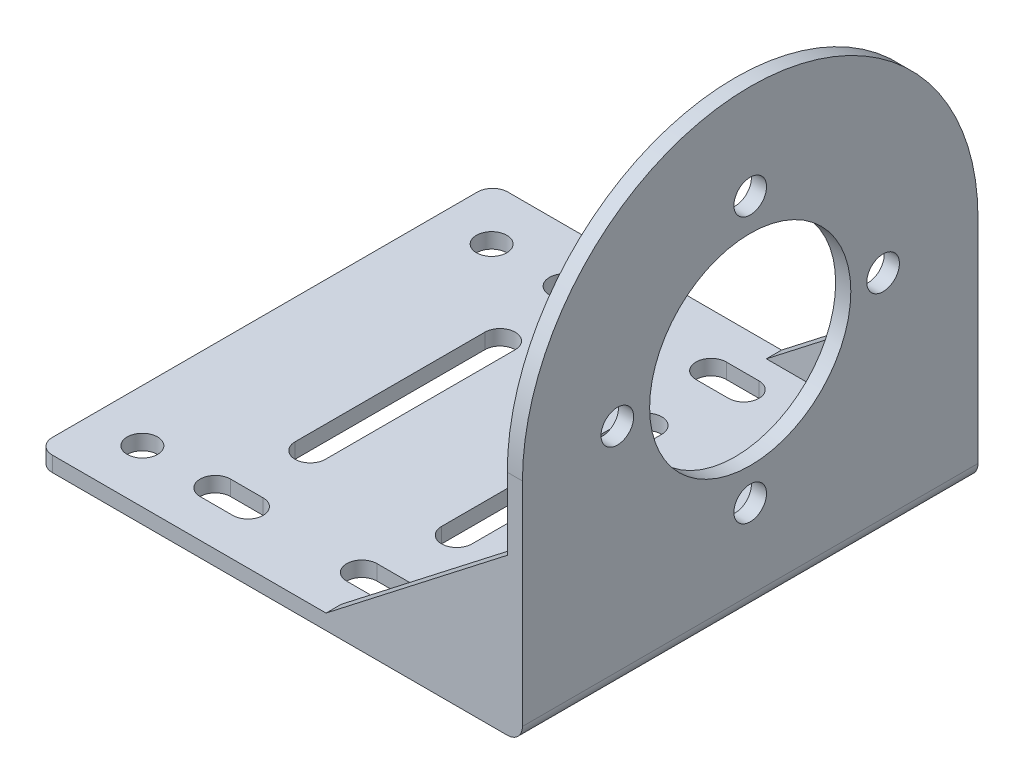
SolidWorks part; units mm, degrees
ref_plane "Front Plane" through (0, 0, 0) normal (0, 0, 1) x (1, 0, 0)
ref_plane "Top Plane" through (0, 0, 0) normal (0, 1, 0) x (1, 0, 0)
ref_plane "Right Plane" through (0, 0, 0) normal (1, 0, 0) x (0, 0, -1)
sketch "Sketch1" plane through (0, 0, 0) normal (1, 0, 0) x (0, 0, -1)
  line L0 (0, 0) -> (60, 0)
  line L1 (60, 0) -> (60, 30)
  line L2 (0, 30) -> (0, 0)
  arc A0 (60, 30) -> (0, 30) centre (30, 30) ccw
  circle A1 centre (30, 30) radius 17.5 construction
  circle A2 centre (30, 47.5) radius 2.15
  circle A6 centre (30, 30) radius 13.25
  circle A10 centre (47.5, 30) radius 2.15
  circle A11 centre (30, 12.5) radius 2.15
  circle A12 centre (12.5, 30) radius 2.15
  point P5 (30, 60)
  dimension "D2" = 35
  dimension "D3" = 4.3
  dimension "D5" = 26.5
  dimension "D1" = 60
  dimension "D6" = 30
  dimension "D4" = 4
extrude "Boss-Extrude1" add sketch "Sketch1" along normal blind 2
sketch "Sketch2" plane through (0, 0, 0) normal (0, 1, 0) x (1, 0, 0)
  line L0 (2, 0) -> (-61.93, 0)
  line L1 (-61.93, 0) -> (-61.93, 60)
  line L2 (-61.93, 60) -> (2, 60)
  line L3 (2, 0) -> (2, 60) construction
  line L4 (2, 60) -> (2, 0)
  line L5 (-61.93, 30) -> (28.4934, 30) construction
  line L6 (-21.85, 53) -> (-26.15, 53) construction
  line L7 (-21.85, 51) -> (-26.15, 51)
  line L8 (-21.85, 55) -> (-26.15, 55)
  line L9 (-41.15, 53) -> (-45.45, 53) construction
  line L10 (-41.15, 51) -> (-45.45, 51)
  line L11 (-41.15, 55) -> (-45.45, 55)
  line L12 (-41.15, 7) -> (-45.45, 7) construction
  line L13 (-41.15, 9) -> (-45.45, 9)
  line L14 (-41.15, 5) -> (-45.45, 5)
  line L15 (-21.85, 7) -> (-26.15, 7) construction
  line L16 (-21.85, 9) -> (-26.15, 9)
  line L17 (-21.85, 5) -> (-26.15, 5)
  line L18 (-24.15, 42.5) -> (-24.15, 17.5) construction
  line L19 (-22.15, 42.5) -> (-22.15, 17.5)
  line L20 (-26.15, 42.5) -> (-26.15, 17.5)
  line L21 (-43.45, 42.5) -> (-43.45, 17.5) construction
  line L24 (-41.45, 42.5) -> (-41.45, 17.5)
  line L25 (-45.45, 42.5) -> (-45.45, 17.5)
  circle A0 centre (-12, 53) radius 2
  arc A1 (-21.85, 51) -> (-21.85, 55) centre (-21.85, 53) ccw
  arc A2 (-26.15, 55) -> (-26.15, 51) centre (-26.15, 53) ccw
  arc A3 (-41.15, 51) -> (-41.15, 55) centre (-41.15, 53) ccw
  arc A4 (-45.45, 55) -> (-45.45, 51) centre (-45.45, 53) ccw
  circle A5 centre (-55.0595, 53) radius 2
  circle A6 centre (-55.0595, 7) radius 2
  arc A7 (-41.15, 9) -> (-41.15, 5) centre (-41.15, 7) cw
  arc A8 (-45.45, 5) -> (-45.45, 9) centre (-45.45, 7) cw
  arc A9 (-21.85, 9) -> (-21.85, 5) centre (-21.85, 7) cw
  arc A10 (-26.15, 5) -> (-26.15, 9) centre (-26.15, 7) cw
  circle A11 centre (-12, 7) radius 2
  arc A12 (-22.15, 42.5) -> (-26.15, 42.5) centre (-24.15, 42.5) ccw
  arc A13 (-26.15, 17.5) -> (-22.15, 17.5) centre (-24.15, 17.5) ccw
  arc A16 (-41.45, 42.5) -> (-45.45, 42.5) centre (-43.45, 42.5) ccw
  arc A17 (-45.45, 17.5) -> (-41.45, 17.5) centre (-43.45, 17.5) ccw
  point P12 (-24, 53)
  point P19 (-43.3, 53)
  point P28 (-24.15, 30)
  point P35 (-43.3, 7)
  point P42 (-24, 7)
  point P55 (-43.45, 30)
  dimension "D6" = 4
  dimension "D7" = 9.85
  dimension "D8" = 2
  dimension "D10" = 2
  dimension "D12" = 4
  dimension "D17" = 2
  dimension "D18" = 2
  dimension "D1" = 63.93
  dimension "D2" = 60
  dimension "D3" = 23
  dimension "D4" = 14
  dimension "D5" = 4.3
  dimension "D9" = 4.3
  dimension "D11" = 15
  dimension "D13" = 6.8705
  dimension "D14" = 7
  dimension "D15" = 25
  dimension "D16" = 25
  dimension "D19" = 18.48
  dimension "D20" = 19.3
extrude "Boss-Extrude2" add sketch "Sketch2" along normal blind 2
sketch "Sketch3" plane through (0, 0, -60) normal (0, 0, -1) x (-1, 0, 0)
  line L0 (0, 20.5251) -> (23.871, 2)
  line L1 (0, 2) -> (0, 30) construction
  line L2 (0, 2) -> (61.93, 2) construction
  line L3 (23.871, 2) -> (0, 2)
  line L4 (0, 2) -> (0, 20.5251)
extrude "Boss-Extrude3" add sketch "Sketch3" against normal blind 2
sketch "Sketch4" plane through (0, 0, 0) normal (0, 0, 1) x (1, 0, 0)
  line L0 (0, 20.5251) -> (-23.871, 2)
  line L1 (-23.871, 2) -> (0, 2)
  line L2 (0, 2) -> (0, 20.5251)
extrude "Boss-Extrude4" add sketch "Sketch4" against normal blind 2
fillet "Fillet1" radius 2 3 edges at (-61.93, 1, 0) (-61.93, 1, -60) (2, 0, -30)
